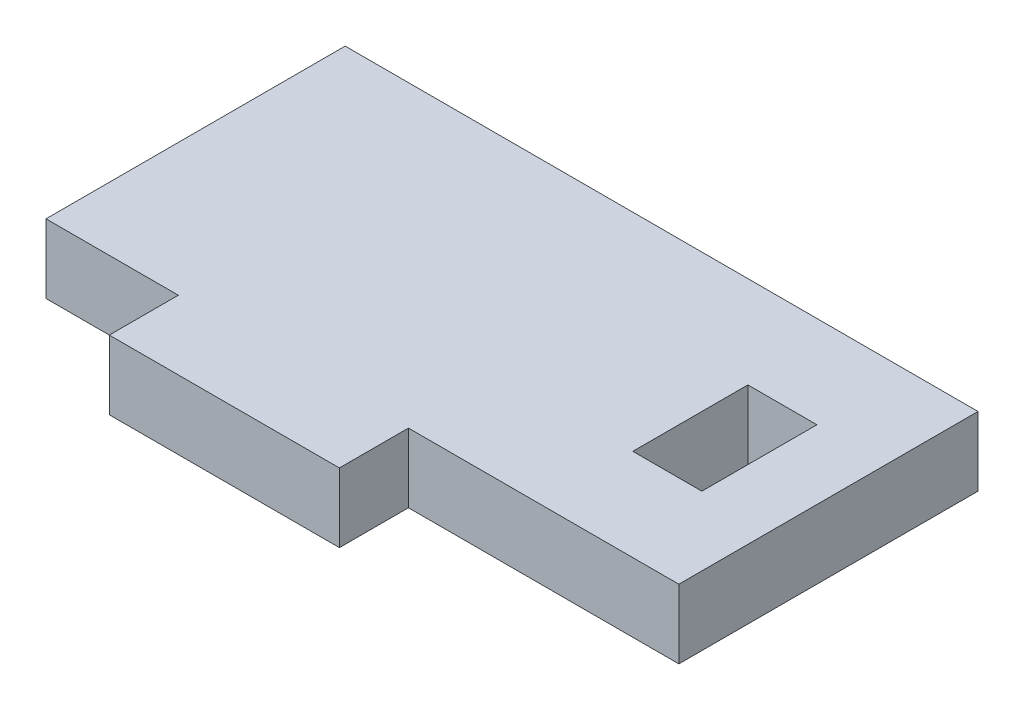
SolidWorks part; units mm, degrees
ref_plane "Front Plane" through (0, 0, 0) normal (0, 0, 1) x (1, 0, 0)
ref_plane "Top Plane" through (0, 0, 0) normal (0, 1, 0) x (1, 0, 0)
ref_plane "Right Plane" through (0, 0, 0) normal (1, 0, 0) x (0, 0, -1)
sketch "Sketch1" plane through (0, 0, 0) normal (0, 1, 0) x (1, 0, 0)
  line L0 (-21.75, 0) -> (-21.75, -3)
  line L1 (-27.5, 13) -> (0, 13)
  line L2 (-27.5, 13) -> (-27.5, 0)
  line L3 (-27.5, 0) -> (-21.75, 0)
  line L4 (0, 13) -> (0, 0)
  line L5 (-21.75, -3) -> (-11.75, -3)
  line L6 (-11.75, -3) -> (-11.75, 0)
  line L7 (-11.75, 0) -> (0, 0)
  line L10 (-3, 9) -> (-6, 9)
  line L11 (-6, 9) -> (-6, 4)
  line L12 (-6, 4) -> (-3, 4)
  line L13 (-3, 4) -> (-3, 9)
  point P5 (-21.75, 0)
  point P11 (0, 0)
  point P15 (0, 0)
  point P16 (0, 0)
  point P17 (0, 0)
  point P18 (0, 0)
  point P19 (6.7319, 16.7355)
  dimension "D1" = 27.5
  dimension "D2" = 13
  dimension "D3" = 5.75
  dimension "D4" = 10
  dimension "D5" = 3
  dimension "D6" = 5
  dimension "D7" = 3
  dimension "D8" = 3
  dimension "D9" = 4
extrude "Boss-Extrude1" add sketch "Sketch1" along normal blind 3
